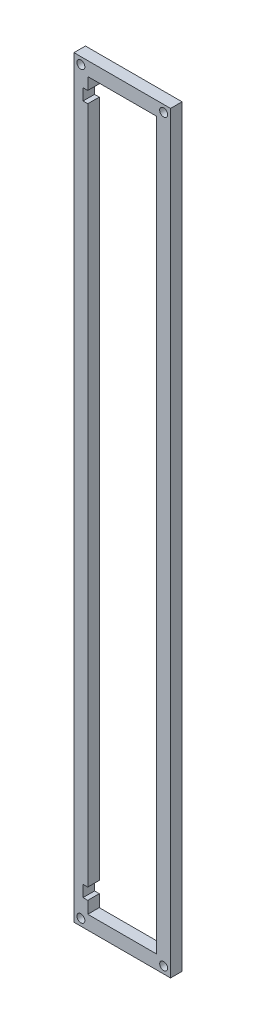
SolidWorks part; units mm, degrees
material "Acrylic (Medium-high impact)"
ref_plane "Front Plane" through (0, 0, 0) normal (0, 0, 1) x (1, 0, 0)
ref_plane "Top Plane" through (0, 0, 0) normal (0, 1, 0) x (1, 0, 0)
ref_plane "Right Plane" through (0, 0, 0) normal (1, 0, 0) x (0, 0, -1)
sketch "Sketch1" plane through (0, 0, 0) normal (0, 0, 1) x (1, 0, 0)
  line L0 (-150.9993, 412.3641) -> (-150.9993, -3.5609) construction
  line L1 (-174.9014, 412.3641) -> (-121.5614, 412.3641)
  line L2 (-174.9014, 412.3641) -> (-174.9014, -3.5609)
  line L3 (-174.9014, -3.5609) -> (-121.5614, -3.5609)
  line L4 (-121.5614, 412.3641) -> (-121.5614, -3.5609)
  point P0 (-153.3114, 202.8141)
  dimension "D1" = 415.925
  dimension "D2" = 53.34
extrude "Boss-Extrude2" add sketch "Sketch1" along normal blind 6.35
sketch "Sketch2" plane through (0, 0, 0) normal (0, 0, -1) x (-1, 0, 0)
  line L0 (174.9014, 412.3641) -> (121.5614, -3.5609) construction
  line L2 (129.1814, 404.7441) -> (167.2814, 404.7441)
  line L3 (129.1814, 404.7441) -> (129.1814, 4.0591)
  line L4 (129.1814, 4.0591) -> (167.2814, 4.0591)
  line L5 (167.2814, 404.7441) -> (167.2814, 4.0591)
  line L6 (129.1814, 404.7441) -> (167.2814, 4.0591) construction
  line L7 (129.1814, 4.0591) -> (167.2814, 404.7441) construction
  line L8 (174.9014, -3.5609) -> (121.5614, -3.5609) construction
  line L9 (174.9014, 412.3641) -> (174.9014, -3.5609) construction
  point P4 (148.2314, 204.4016)
  dimension "D1" = 7.62
  dimension "D2" = 7.62
extrude "Cut-Extrude1" cut sketch "Sketch2" against normal through all
hole_wizard "#17 (0.173) Diameter Hole1" positions "Sketch3" profile "Sketch4" hole size "#17" standard "ANSI Inch" end condition through all
sketch "Sketch3" plane through (0, 0, 0) normal (0, 0, -1) x (-1, 0, 0)
  line L0 (174.9014, 412.3641) -> (121.5614, -3.5609) construction
  line L3 (125.3714, 408.5541) -> (171.0914, 408.5541) construction
  line L4 (125.3714, 408.5541) -> (125.3714, 0.2491) construction
  line L5 (125.3714, 0.2491) -> (171.0914, 0.2491) construction
  line L6 (171.0914, 408.5541) -> (171.0914, 0.2491) construction
  line L7 (125.3714, 408.5541) -> (171.0914, 0.2491) construction
  line L8 (125.3714, 0.2491) -> (171.0914, 408.5541) construction
  line L9 (174.9014, 412.3641) -> (174.9014, -3.5609) construction
  line L10 (121.5614, 412.3641) -> (174.9014, 412.3641) construction
  point P5 (148.2314, 204.4016)
  point P6 (171.0914, 0.2491)
  point P103 (125.3714, 408.5541)
  point P104 (125.3714, 0.2491)
  point P105 (171.0914, 408.5541)
  dimension "D1" = 3.81
  dimension "D2" = 3.81
sketch "Sketch4" plane through (-171.0914, 408.5541, 0) normal (1, 0, 0) x (0, 1, 0)
  line L0 (0, 0) -> (0, 6.35)
  line L1 (0, 6.35) -> (2.1971, 6.35)
  line L2 (2.1971, 6.35) -> (2.1971, 0)
  line L5 (2.1971, 0) -> (0, 0)
  line L11 (0, -6.35) -> (0, 107.95) construction
  dimension "Thru Hole Dia." = 4.3942
  dimension "Thru Hole Depth" = 6.35
sketch "Sketch5" plane through (0, 0, 6.35) normal (0, 0, 1) x (1, 0, 0)
  line L0 (-167.2814, 4.0591) -> (-167.2814, 404.7441) construction
  line L1 (-169.9008, 391.7266) -> (-167.2814, 391.7266)
  line L2 (-169.9008, 391.7266) -> (-169.9008, 398.0766)
  line L3 (-169.9008, 398.0766) -> (-167.2814, 398.0766)
  line L4 (-167.2814, 391.7266) -> (-167.2814, 398.0766)
  line L6 (-169.9008, 10.7266) -> (-167.2814, 10.7266)
  line L7 (-169.9008, 10.7266) -> (-169.9008, 17.0766)
  line L8 (-169.9008, 17.0766) -> (-167.2814, 17.0766)
  line L9 (-167.2814, 10.7266) -> (-167.2814, 17.0766)
extrude "Cut-Extrude2" cut sketch "Sketch5" against normal through all and the other way through all
